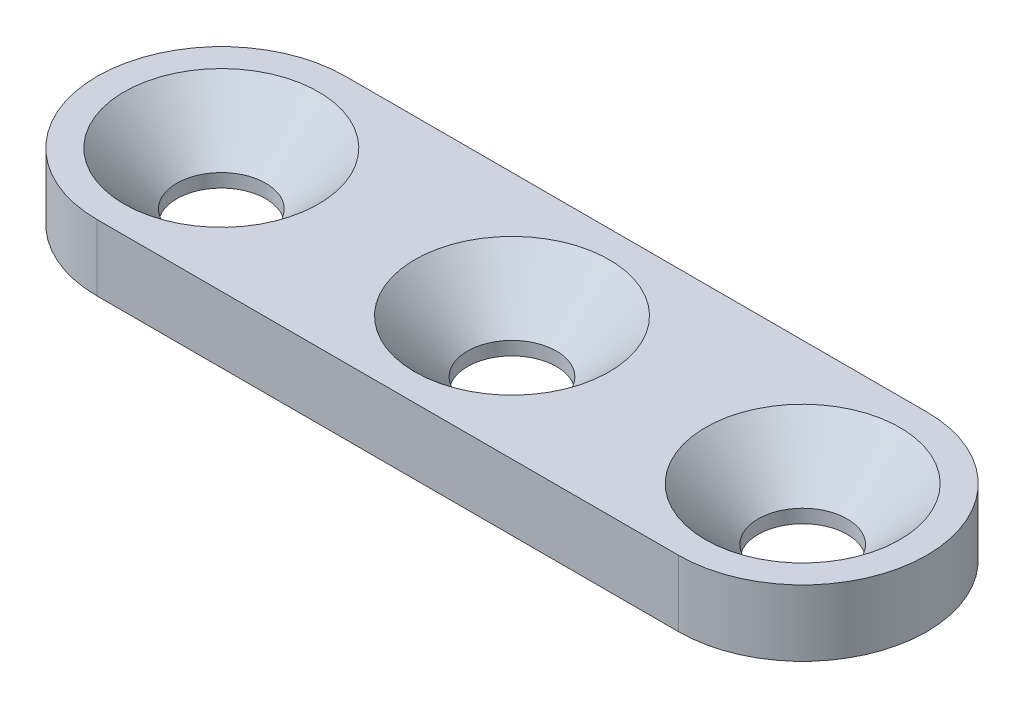
SolidWorks part; units mm, degrees
ref_plane "Front Plane" through (0, 0, 0) normal (0, 0, 1) x (1, 0, 0)
ref_plane "Top Plane" through (0, 0, 0) normal (0, 1, 0) x (1, 0, 0)
ref_plane "Right Plane" through (0, 0, 0) normal (1, 0, 0) x (0, 0, -1)
sketch "Sketch3" plane through (0, 0, 0) normal (0, 1, 0) x (1, 0, 0)
  line L1 (-14.05, 6) -> (14.05, 6)
  line L3 (-14.05, -6) -> (14.05, -6)
  arc A0 (-14.05, 6) -> (-14.05, -6) centre (-14.05, 0) ccw
  arc A1 (14.05, 6) -> (14.05, -6) centre (14.05, 0) cw
  point P0 (0, 0)
  dimension "D3" = 6
  dimension "D4" = 6
  dimension "D1" = 28.1
  dimension "D2" = 14.05
  dimension "D5" = 14.05
extrude "Boss-Extrude2" add sketch "Sketch3" along normal blind 3.2
sketch "Sketch4" plane through (0, 3.2, 0) normal (0, 1, 0) x (1, 0, 0)
  circle A0 centre (0, 0) radius 2.1
  circle A1 centre (14.05, 0) radius 2.1
  circle A2 centre (-14.05, 0) radius 2.1
  point P0 (0, 0)
  point P2 (14.05, 0)
  point P6 (-14.05, 0)
  dimension "D1" = 4.2
hole_wizard "CSK for M4 Countersunk Flat Head1" positions "Sketch4" profile "Sketch5" countersink size "M4" standard "BSI" end condition through all
sketch "Sketch5" plane through (0, 3.2, 0) normal (1, 0, 0) x (0, 0, 1)
  line L0 (0, 0) -> (0, 3.2)
  line L1 (0, 3.2) -> (2.15, 3.2)
  line L2 (2.15, 3.2) -> (2.15, 2.55)
  line L3 (2.15, 2.55) -> (4.7, 0)
  line L5 (4.7, 0) -> (0, 0)
  line L6 (-2.15, 2.55) -> (-4.7, 0) construction
  line L11 (0, -6.35) -> (0, 107.95) construction
  dimension "Thru Hole Dia." = 4.3
  dimension "Thru Hole Depth" = 3.2
  dimension "Near C'Sink Dia." = 9.4
  dimension "Near C'Sink Angle" = 90
